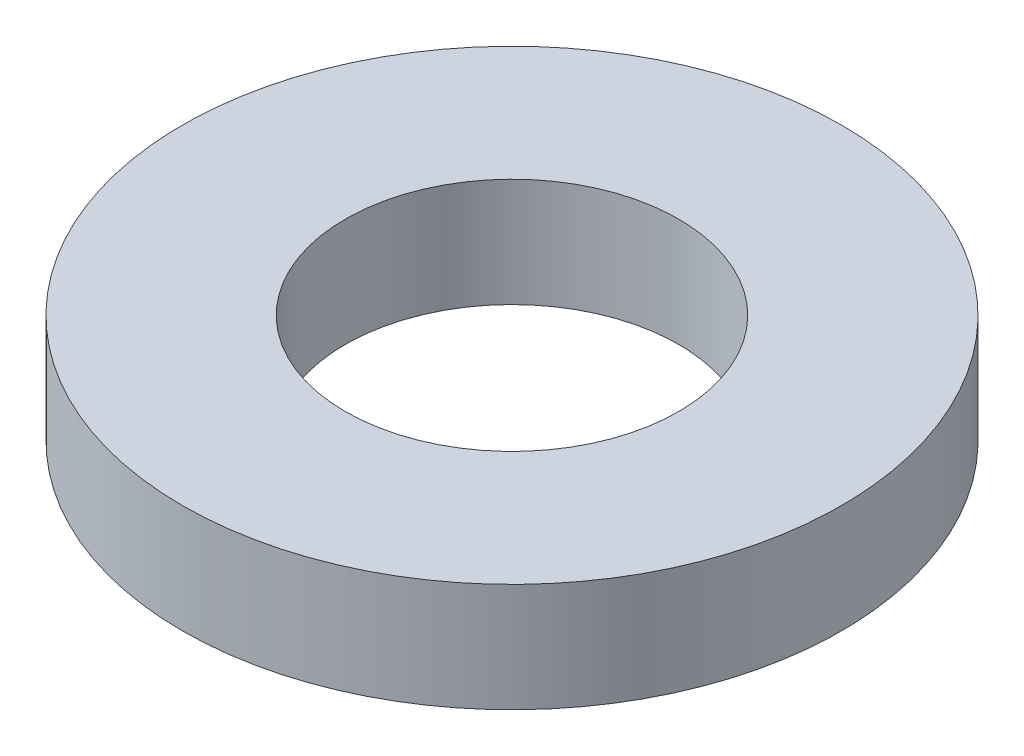
SolidWorks part; units mm, degrees
ref_plane "前视基准面" through (0, 0, 0) normal (0, 0, 1) x (1, 0, 0)
ref_plane "上视基准面" through (0, 0, 0) normal (0, 1, 0) x (1, 0, 0)
ref_plane "右视基准面" through (0, 0, 0) normal (1, 0, 0) x (0, 0, -1)
sketch "草图1" plane through (0, 0, 0) normal (0, 1, 0) x (1, 0, 0)
  circle A0 centre (0, 0) radius 2.15
  circle A1 centre (0, 0) radius 4.25
  dimension "D1" = 4.3
  dimension "D2" = 8.5
extrude "凸台-拉伸1" add sketch "草图1" along normal blind 1.4
